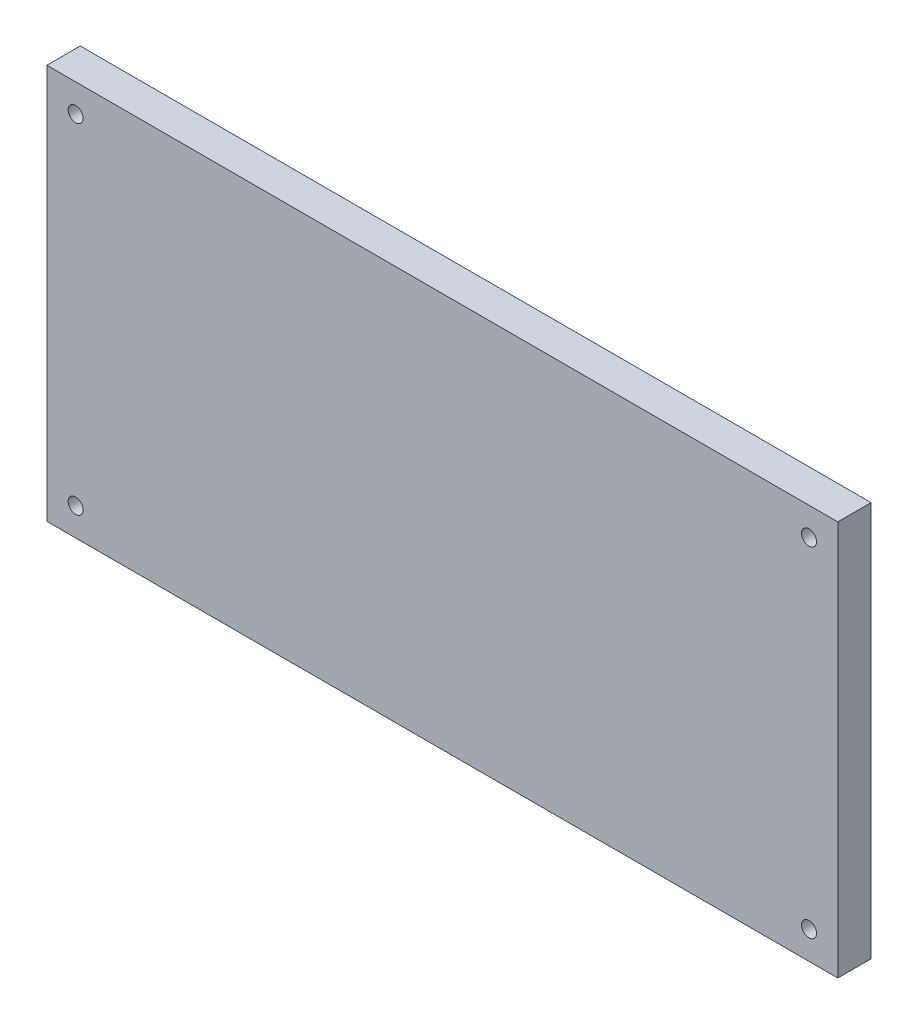
SolidWorks part; units mm, degrees
ref_plane "Plan de face" through (0, 0, 0) normal (0, 0, 1) x (1, 0, 0)
ref_plane "Plan de dessus" through (0, 0, 0) normal (0, 1, 0) x (1, 0, 0)
ref_plane "Plan de droite" through (0, 0, 0) normal (1, 0, 0) x (0, 0, -1)
sketch "Esquisse1" plane through (0, 0, 0) normal (0, 0, 1) x (1, 0, 0)
  line L0 (0, 23.7) -> (94.9, 23.7) construction
  line L1 (0, 0) -> (94.9, 0)
  line L2 (0, 0) -> (0, 47.4)
  line L3 (0, 47.4) -> (94.9, 47.4)
  line L4 (94.9, 0) -> (94.9, 47.4)
  line L5 (47.45, 47.4) -> (47.45, 0) construction
  line L7 (3.45, 3.35) -> (91.45, 3.35) construction
  line L8 (3.45, 3.35) -> (3.45, 44.05) construction
  line L9 (3.45, 44.05) -> (91.45, 44.05) construction
  line L10 (91.45, 3.35) -> (91.45, 44.05) construction
  line L11 (3.45, 3.35) -> (91.45, 44.05) construction
  line L12 (3.45, 44.05) -> (91.45, 3.35) construction
  circle A0 centre (3.45, 44.05) radius 0.9
  circle A1 centre (3.45, 3.35) radius 0.9
  circle A2 centre (91.45, 3.35) radius 0.9
  circle A3 centre (91.45, 44.05) radius 0.9
  point P9 (47.45, 23.7)
  dimension "D1" = 94.9
  dimension "D2" = 47.4
  dimension "D3" = 40.7
  dimension "D4" = 88
extrude "Boss.-Extru.1" add sketch "Esquisse1" along normal blind 4
